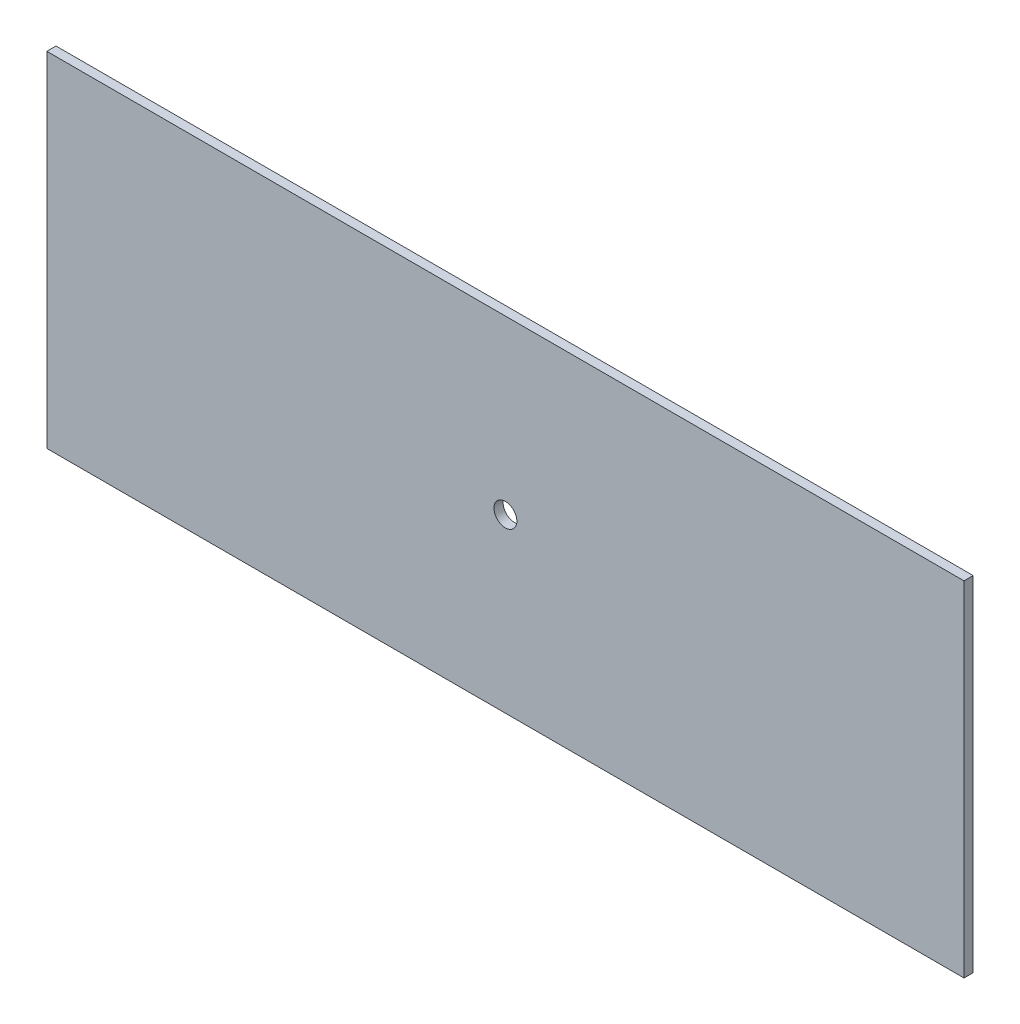
SolidWorks part; units mm, degrees
ref_plane "Front Plane" through (0, 0, 0) normal (0, 0, 1) x (1, 0, 0)
ref_plane "Top Plane" through (0, 0, 0) normal (0, 1, 0) x (1, 0, 0)
ref_plane "Right Plane" through (0, 0, 0) normal (1, 0, 0) x (0, 0, -1)
sketch "Sketch1" plane through (0, 0, 0) normal (0, 0, 1) x (1, 0, 0)
  line L1 (0, 0) -> (400, 0)
  line L2 (0, 0) -> (0, -150)
  line L3 (0, -150) -> (400, -150)
  line L4 (400, 0) -> (400, -150)
  circle A0 centre (200, -75) radius 5
  dimension "D1" = 400
  dimension "D2" = 150
extrude "Boss-Extrude1" add sketch "Sketch1" along normal blind 4
